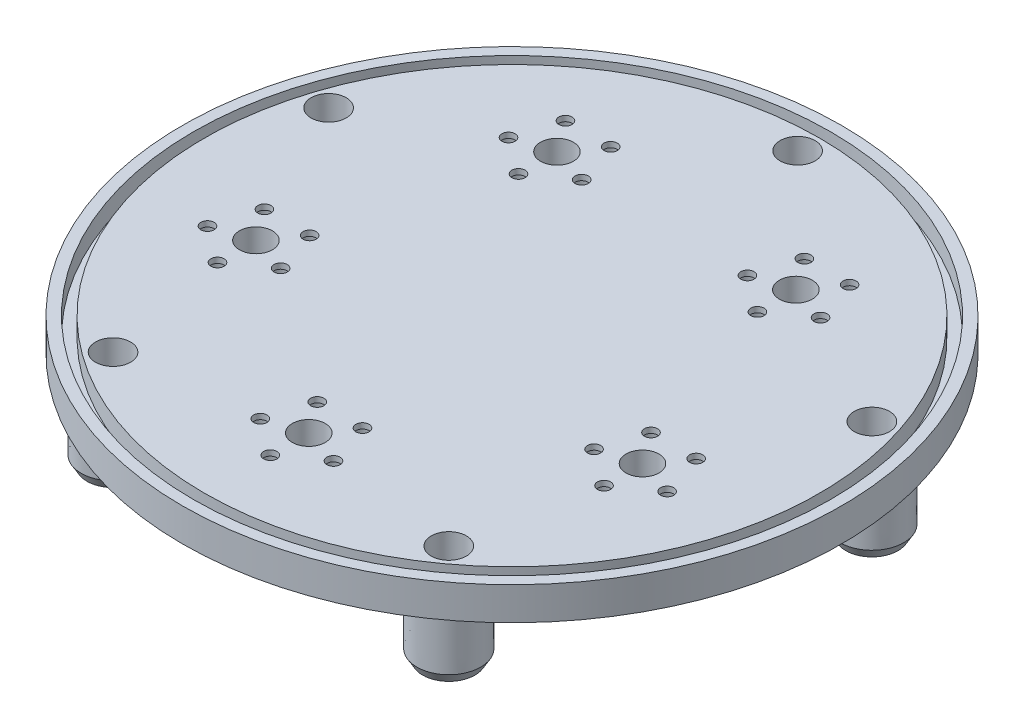
SolidWorks part; units mm, degrees
ref_plane "Front Plane" through (0, 0, 0) normal (0, 0, 1) x (1, 0, 0)
ref_plane "Top Plane" through (0, 0, 0) normal (0, 1, 0) x (1, 0, 0)
ref_plane "Right Plane" through (0, 0, 0) normal (1, 0, 0) x (0, 0, -1)
sketch "Sketch1" plane through (0, 0, 0) normal (0, 1, 0) x (1, 0, 0)
  circle A14 centre (0, 0) radius 30
extrude "Boss-Extrude1" add sketch "Sketch1" along normal blind 3
sketch "Sketch2" plane through (0, 3, 0) normal (0, -1, 0) x (1, 0, 0)
  line L0 (4, -26) -> (4, -29.7321) construction
  line L1 (-4, -26) -> (-4, -29.7321) construction
  line L2 (-23.4914, -11.8387) -> (-27.0409, -12.992) construction
  line L3 (-25.9635, -4.2302) -> (-29.513, -5.3835) construction
  line L4 (-18.5185, 18.6833) -> (-20.7122, 21.7027) construction
  line L5 (-12.0463, 23.3856) -> (-14.24, 26.4049) construction
  line L6 (12.0463, 23.3856) -> (14.24, 26.4049) construction
  line L7 (18.5185, 18.6833) -> (20.7122, 21.7027) construction
  line L8 (25.9635, -4.2302) -> (29.513, -5.3835) construction
  line L9 (23.4914, -11.8387) -> (27.0409, -12.992) construction
  circle A0 centre (0, -26) radius 3 construction
  arc A2 (4, -26) -> (-4, -26) centre (0, -26) ccw construction
  arc A4 (-23.4914, -11.8387) -> (-25.9635, -4.2302) centre (-24.7275, -8.0344) ccw construction
  circle A5 centre (-24.7275, -8.0344) radius 3 construction
  arc A7 (-18.5185, 18.6833) -> (-12.0463, 23.3856) centre (-15.2824, 21.0344) ccw construction
  circle A8 centre (-15.2824, 21.0344) radius 3 construction
  arc A10 (12.0463, 23.3856) -> (18.5185, 18.6833) centre (15.2824, 21.0344) ccw construction
  circle A11 centre (15.2824, 21.0344) radius 3 construction
  arc A13 (25.9635, -4.2302) -> (23.4914, -11.8387) centre (24.7275, -8.0344) ccw construction
  circle A14 centre (24.7275, -8.0344) radius 3 construction
  circle A16 centre (0, 0) radius 28
  circle A17 centre (0, 0) radius 29
  point P32 (0, 0)
sketch "Sketch5" plane through (0, 0, 0) normal (0, -1, 0) x (1, 0, 0)
  circle A0 centre (0, -26) radius 2.94
  circle A1 centre (-24.7275, -8.0344) radius 2.94
  circle A2 centre (-15.2824, 21.0344) radius 2.94
  circle A4 centre (15.2824, 21.0344) radius 2.94
  circle A6 centre (24.7275, -8.0344) radius 2.94
  point P12 (0, 0)
  dimension "D1" = 5
extrude "Boss-Extrude3" add sketch "Sketch5" along normal blind 6 draft 0.4
sketch "Sketch6" plane through (0, 0, 0) normal (0, -1, 0) x (1, 0, 0)
  line L0 (0, 0) -> (0, 37.9499) construction
  circle A0 centre (0, 0) radius 18.5 construction
  circle A1 centre (0, 18.5) radius 1.5
  circle A2 centre (0, 18.5) radius 3.5 construction
  circle A3 centre (0, 22) radius 0.6
  circle A4 centre (3.3287, 19.5816) radius 0.6
  circle A5 centre (2.0572, 15.6684) radius 0.6
  circle A6 centre (-2.0572, 15.6684) radius 0.6
  circle A7 centre (-3.3287, 19.5816) radius 0.6
  circle A8 centre (17.5945, 5.7168) radius 1.5
  circle A9 centre (20.9232, 6.7984) radius 0.6
  circle A10 centre (19.6518, 2.8853) radius 0.6
  circle A11 centre (15.5373, 2.8853) radius 0.6
  circle A12 centre (14.2658, 6.7984) radius 0.6
  circle A13 centre (17.5945, 9.2168) radius 0.6
  circle A14 centre (17.5945, 5.7168) radius 3.5 construction
  circle A15 centre (10.874, -14.9668) radius 1.5
  circle A16 centre (12.9313, -17.7984) radius 0.6
  circle A17 centre (8.8168, -17.7984) radius 0.6
  circle A18 centre (7.5453, -13.8853) radius 0.6
  circle A19 centre (10.874, -11.4668) radius 0.6
  circle A20 centre (14.2027, -13.8853) radius 0.6
  circle A21 centre (10.874, -14.9668) radius 3.5 construction
  circle A22 centre (-10.874, -14.9668) radius 1.5
  circle A23 centre (-12.9313, -17.7984) radius 0.6
  circle A24 centre (-14.2027, -13.8853) radius 0.6
  circle A25 centre (-10.874, -11.4668) radius 0.6
  circle A26 centre (-7.5453, -13.8853) radius 0.6
  circle A27 centre (-8.8168, -17.7984) radius 0.6
  circle A28 centre (-10.874, -14.9668) radius 3.5 construction
  circle A29 centre (-17.5945, 5.7168) radius 1.5
  circle A30 centre (-20.9232, 6.7984) radius 0.6
  circle A31 centre (-17.5945, 9.2168) radius 0.6
  circle A32 centre (-14.2658, 6.7984) radius 0.6
  circle A33 centre (-15.5373, 2.8853) radius 0.6
  circle A34 centre (-19.6518, 2.8853) radius 0.6
  circle A35 centre (-17.5945, 5.7168) radius 3.5 construction
  point P19 (0, 18.5)
  point P34 (17.5945, 5.7168)
  point P48 (10.874, -14.9668)
  point P62 (-10.874, -14.9668)
  point P76 (-17.5945, 5.7168)
  point P77 (0, 0)
  dimension "D1" = 5
  dimension "D2" = 5
extrude "Cut-Extrude2" cut sketch "Sketch6" against normal through all
sketch "Sketch7" plane through (0, 0, 0) normal (0, -1, 0) x (1, 0, 0)
  line L0 (0, 0) -> (0, 26.0654) construction
  circle A0 centre (0, 0) radius 18.5 construction
  circle A1 centre (0, 18.5) radius 3.5 construction
  circle A2 centre (0, 22) radius 1
  circle A3 centre (3.3287, 19.5816) radius 1
  circle A4 centre (2.0572, 15.6684) radius 1
  circle A5 centre (-2.0572, 15.6684) radius 1
  circle A6 centre (-3.3287, 19.5816) radius 1
  circle A7 centre (20.9232, 6.7984) radius 1
  circle A8 centre (19.6518, 2.8853) radius 1
  circle A9 centre (15.5373, 2.8853) radius 1
  circle A10 centre (14.2658, 6.7984) radius 1
  circle A11 centre (17.5945, 9.2168) radius 1
  circle A12 centre (17.5945, 5.7168) radius 3.5 construction
  circle A13 centre (12.9313, -17.7984) radius 1
  circle A14 centre (8.8168, -17.7984) radius 1
  circle A15 centre (7.5453, -13.8853) radius 1
  circle A16 centre (10.874, -11.4668) radius 1
  circle A17 centre (14.2027, -13.8853) radius 1
  circle A18 centre (10.874, -14.9668) radius 3.5 construction
  circle A19 centre (-12.9313, -17.7984) radius 1
  circle A20 centre (-14.2027, -13.8853) radius 1
  circle A21 centre (-10.874, -11.4668) radius 1
  circle A22 centre (-7.5453, -13.8853) radius 1
  circle A23 centre (-8.8168, -17.7984) radius 1
  circle A24 centre (-10.874, -14.9668) radius 3.5 construction
  circle A25 centre (-20.9232, 6.7984) radius 1
  circle A26 centre (-17.5945, 9.2168) radius 1
  circle A27 centre (-14.2658, 6.7984) radius 1
  circle A28 centre (-15.5373, 2.8853) radius 1
  circle A29 centre (-19.6518, 2.8853) radius 1
  circle A30 centre (-17.5945, 5.7168) radius 3.5 construction
  point P20 (0, 18.5)
  point P33 (17.5945, 5.7168)
  point P46 (10.874, -14.9668)
  point P59 (-10.874, -14.9668)
  point P72 (-17.5945, 5.7168)
  point P73 (0, 0)
  dimension "D1" = 5
  dimension "D2" = 5
extrude "Cut-Extrude3" cut sketch "Sketch7" against normal blind 2.5
sketch "Sketch8" plane through (0, 0, 0) normal (0, -1, 0) x (1, 0, 0)
  line L0 (-11.1765, 8.5525) -> (-2.9522, 7.294)
  line L3 (-11.4261, 6.9215) -> (-3.2018, 5.663)
  line L5 (-3.3228, 4.8722) -> (-11.5471, 6.1307)
  line L6 (-3.5724, 3.2412) -> (-11.7966, 4.4997)
  line L7 (-11.4261, 6.9215) -> (-11.1765, 8.5525)
  line L8 (-11.5471, 6.1307) -> (-11.7966, 4.4997)
  line L9 (-11.4866, 6.5261) -> (-13.2658, 6.7984) construction
  line L10 (-11.5471, 6.1307) -> (-11.4261, 6.9215) construction
  line L11 (-13.2658, 6.7984) -> (-15.2658, 6.7984) construction
  line L12 (1.9786, 4.3991) -> (0.6341, 12.6098)
  line L13 (3.607, 4.6658) -> (2.2624, 12.8764)
  line L14 (2.2624, 12.8764) -> (0.6341, 12.6098)
  line L15 (4.6802, 13.2723) -> (6.0248, 5.0617)
  line L16 (3.0519, 13.0057) -> (4.6802, 13.2723)
  line L17 (3.0519, 13.0057) -> (4.3964, 4.795)
  line L18 (4.7952, -0.5224) -> (12.1885, 3.2936)
  line L19 (5.552, -1.9886) -> (12.9453, 1.8273)
  line L20 (12.9453, 1.8273) -> (12.1885, 3.2936)
  line L21 (14.069, -0.3498) -> (6.6757, -4.1657)
  line L22 (13.3122, 1.1165) -> (14.069, -0.3498)
  line L23 (13.3122, 1.1165) -> (5.9189, -2.6995)
  line L24 (0.985, -4.722) -> (6.8988, -10.5742)
  line L25 (-0.1756, -5.8948) -> (5.7382, -11.747)
  line L26 (5.7382, -11.747) -> (6.8988, -10.5742)
  line L27 (4.0149, -13.4885) -> (-1.8989, -7.6363)
  line L28 (5.1755, -12.3157) -> (4.0149, -13.4885)
  line L29 (5.1755, -12.3157) -> (-0.7383, -6.4634)
  line L30 (-4.1865, -2.3959) -> (-7.9248, -9.8288)
  line L31 (-5.6606, -1.6546) -> (-9.3989, -9.0874)
  line L32 (-9.3989, -9.0874) -> (-7.9248, -9.8288)
  line L33 (-11.5876, -7.9866) -> (-7.8493, -0.5537)
  line L34 (-10.1136, -8.728) -> (-11.5876, -7.9866)
  line L35 (-10.1136, -8.728) -> (-6.3753, -1.2951)
  arc A0 (-3.3228, 4.8722) -> (-3.2018, 5.663) centre (-3.2623, 5.2676) ccw
  arc A1 (-3.5724, 3.2412) -> (-2.9522, 7.294) centre (-3.2623, 5.2676) ccw
  circle A3 centre (-14.2658, 6.7984) radius 1 construction
  circle A4 centre (0, 18.25) radius 9 construction
  circle A6 centre (17.3568, 5.6396) radius 9 construction
  circle A7 centre (10.7271, -14.7646) radius 9 construction
  circle A8 centre (-10.7271, -14.7646) radius 9 construction
  circle A9 centre (-17.3568, 5.6396) radius 9 construction
  circle A12 centre (3.8794, 5.3395) radius 3 construction
  circle A13 centre (6.277, -2.0395) radius 3 construction
  circle A14 centre (0, -6.6) radius 3 construction
  circle A15 centre (-6.277, -2.0395) radius 3 construction
  circle A16 centre (-3.8794, 5.3395) radius 3 construction
  arc A17 (1.9786, 4.3991) -> (6.0248, 5.0617) centre (4.0017, 4.7304) ccw
  arc A18 (3.607, 4.6658) -> (4.3964, 4.795) centre (4.0017, 4.7304) ccw
  arc A19 (4.7952, -0.5224) -> (6.6757, -4.1657) centre (5.7355, -2.3441) ccw
  arc A20 (5.552, -1.9886) -> (5.9189, -2.6995) centre (5.7355, -2.3441) ccw
  arc A21 (0.985, -4.722) -> (-1.8989, -7.6363) centre (-0.457, -6.1791) ccw
  arc A22 (-0.1756, -5.8948) -> (-0.7383, -6.4634) centre (-0.457, -6.1791) ccw
  arc A23 (-4.1865, -2.3959) -> (-7.8493, -0.5537) centre (-6.0179, -1.4748) ccw
  arc A24 (-5.6606, -1.6546) -> (-6.3753, -1.2951) centre (-6.0179, -1.4748) ccw
  point P34 (0, 0)
  point P45 (0, 0)
  point P82 (0, 0)
  dimension "D1" = 5
extrude "Cut-Extrude4" cut sketch "Sketch8" against normal blind 1.7
sketch "Sketch9" plane through (0, -6, 0) normal (0, -1, 0) x (1, 0, 0)
  circle A0 centre (-24.7275, -8.0344) radius 1.6
  circle A1 centre (-15.2824, 21.0344) radius 1.6
  circle A2 centre (15.2824, 21.0344) radius 1.6
  circle A3 centre (24.7275, -8.0344) radius 1.6
  circle A4 centre (0, -26) radius 1.6
  point P13 (0, 0)
  dimension "D1" = 5
extrude "Cut-Extrude5" cut sketch "Sketch9" against normal through all
chamfer "Chamfer1" distance 0.9 angle 30 5 edges at (0, -6, -28.8981) (24.7275, -6, -10.9326) (15.2824, -6, 18.1363) (-15.2824, -6, 18.1363) (-24.7275, -6, -10.9326)
extrude "Cut-Extrude6" cut sketch "Sketch2" along normal blind 1.7
